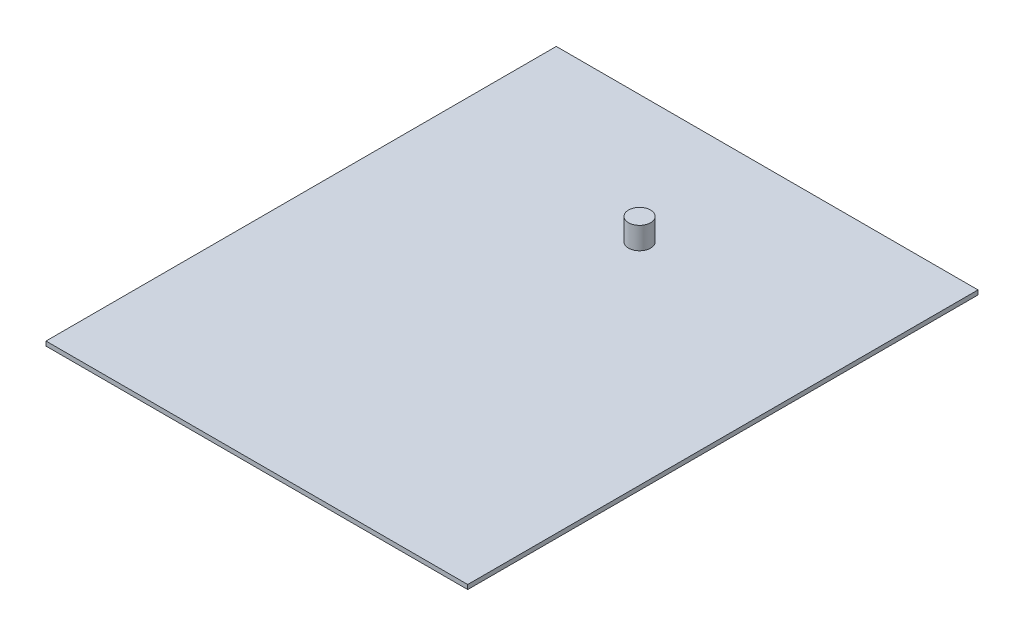
SolidWorks part; units mm, degrees
ref_plane "Front Plane" through (0, 0, 0) normal (0, 0, 1) x (1, 0, 0)
ref_plane "Top Plane" through (0, 0, 0) normal (0, 1, 0) x (1, 0, 0)
ref_plane "Right Plane" through (0, 0, 0) normal (1, 0, 0) x (0, 0, -1)
sketch "草图1" plane through (0, 0, 0) normal (0, 1, 0) x (1, 0, 0)
  line L1 (95.7, -115.8) -> (-95.7, -115.8)
  line L2 (95.7, -115.8) -> (95.7, 115.8)
  line L3 (95.7, 115.8) -> (-95.7, 115.8)
  line L4 (-95.7, -115.8) -> (-95.7, 115.8)
  line L5 (95.7, -115.8) -> (-95.7, 115.8) construction
  line L6 (95.7, 115.8) -> (-95.7, -115.8) construction
  point P0 (0, 0)
  dimension "D1" = 191.4
  dimension "D2" = 231.6
extrude "凸台-拉伸1" add sketch "草图1" along normal blind 2
sketch "草图2" plane through (0, 2, 0) normal (0, 1, 0) x (1, 0, 0)
  circle A1 centre (0, 57.9) radius 5
extrude "凸台-拉伸2" add sketch "草图2" along normal blind 10
